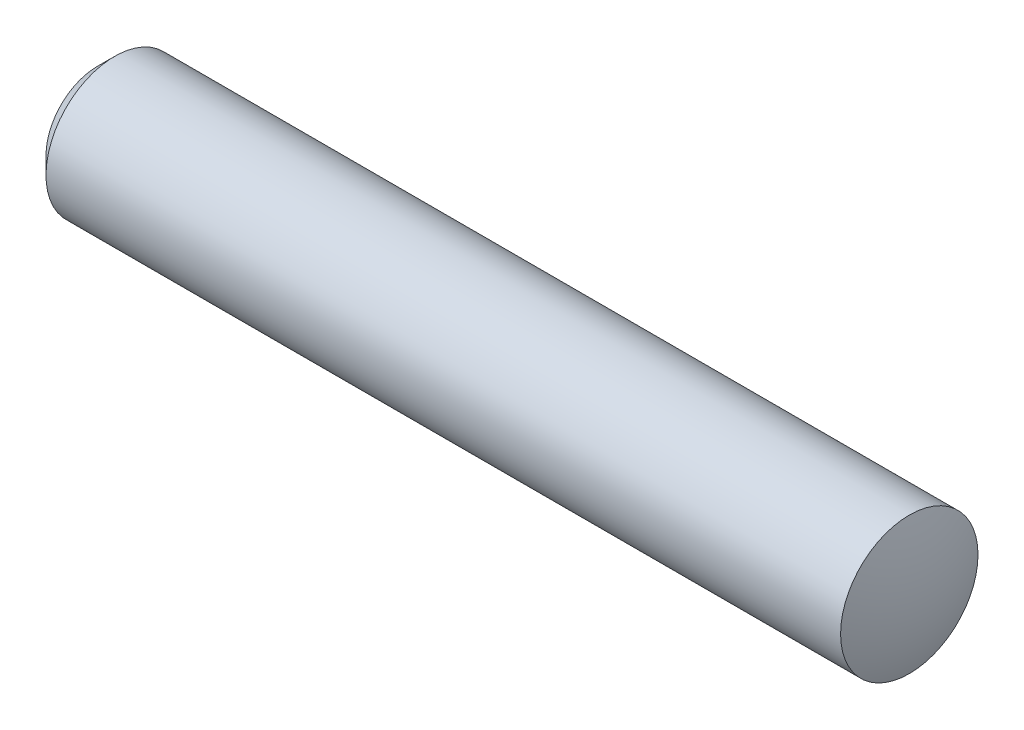
SolidWorks part; units mm, degrees
ref_plane "Front" through (0, 0, 0) normal (0, 0, 1) x (1, 0, 0)
ref_plane "Top" through (0, 0, 0) normal (0, 1, 0) x (1, 0, 0)
ref_plane "Right" through (0, 0, 0) normal (1, 0, 0) x (0, 0, -1)
sketch "Sketch1" plane through (0, 0, 0) normal (0, 0, 1) x (1, 0, 0)
  line L0 (-11.8977, 0) -> (11.8977, 0) construction
  line L1 (-12.1023, 1.5) -> (-11.6023, 2)
  line L2 (-11.6023, 2) -> (-6.1023, 2)
  line L3 (11.8977, 0) -> (11.8977, -7.427) construction
  line L4 (-11.8977, 0) -> (-11.8977, -2.1222) construction
  line L5 (-6.1023, 2) -> (-2.1023, 2)
  line L6 (-2.1023, 2) -> (11.5284, 2)
  line L7 (-7.8682, 16.2978) -> (10.1318, 16.2978) construction
  line L8 (-11.8977, 0) -> (-2.1023, 0)
  line L9 (-4.1023, 2) -> (-4.1023, 0) construction
  line L10 (-12.1023, 1.5) -> (-6.1023, 1.5) construction
  line L11 (-6.1023, 1.5) -> (-6.1023, 2) construction
  line L12 (-2.1023, 0) -> (11.8977, 0)
  line L13 (4.8977, 0) -> (4.8977, -0.4) construction
  line L14 (-9.1023, 1.5) -> (-9.1023, -0.4) construction
  line L15 (-9.1023, -0.4) -> (4.8977, -0.4) construction
  arc A0 (11.5284, 2) -> (11.8977, 0) centre (6.2977, 0) cw
  arc A1 (-12.1023, 1.5) -> (-11.8977, 0) centre (-17.4977, 0) cw
  arc A2 (-11.8977, -0.8204) -> (11.5284, -1.6339) centre (-2.1023, -56.45) cw construction
  dimension "re" = 5.6
  dimension "D1" = 0.5
  dimension "D2" = 45
  dimension "d" = 4
  dimension "bm" = 6
  dimension "b" = 14
  dimension "la" = 4
  dimension "l" = 18
  dimension "F" = 0.4
revolve "Revolve1" add sketch "Sketch1" angle 360 about L8
cosmetic thread "Cosmetic Thread1" [suppressed]
cosmetic thread "Cosmetic Thread2" [suppressed]
sketch "Sketch2" plane through (0, 0, 0) normal (0, 0, 1) x (1, 0, 0)
  line L0 (11.5284, 1.5) -> (11.817, 2)
  line L1 (11.817, 2) -> (11.817, 2.5774)
  line L2 (11.817, 2.5774) -> (11.2397, 2.5774)
  line L3 (11.2397, 2.5774) -> (11.2397, 2)
  line L4 (11.2397, 2) -> (11.5284, 1.5)
  line L5 (11.5284, -2) -> (11.5284, 2) construction
  line L6 (0, 0) -> (13.194, 0) construction
  line L7 (-2.1023, 2) -> (11.5284, 2) construction
  dimension "D1" = 3
revolve "Cut-Revolve1" [suppressed] cut sketch "Sketch2" angle 360 about L6
pattern_linear "LPattern1" [suppressed] count 18 along (1, 0, 0)
sketch "Sketch3" plane through (0, 0, 0) normal (0, 0, 1) x (1, 0, 0)
  line L0 (0, 0) -> (-12.6753, 0) construction
  line L1 (-11.6023, 1.5) -> (-11.3136, 2)
  line L2 (-11.3136, 2) -> (-11.3136, 2.5774)
  line L3 (-11.3136, 2.5774) -> (-11.891, 2.5774)
  line L4 (-11.891, 2.5774) -> (-11.891, 2)
  line L5 (-11.891, 2) -> (-11.6023, 1.5)
  line L6 (-11.6023, 2) -> (-6.1023, 2) construction
  line L7 (-11.6023, -2) -> (-11.6023, 2) construction
  dimension "D1" = 3
revolve "Cut-Revolve2" [suppressed] cut sketch "Sketch3" angle 360 about L0
pattern_linear "LPattern2" [suppressed] count 8 spacing 0.8 along (-1, 0, 0)
equation "\"la@Sketch1\" = \"l@Sketch1\" - \"b@Sketch1\""
equation "\"F@Sketch1\" = \"d@Sketch1\" / 10"
equation "\"D1@Cosmetic Thread1\" = \"bm@Sketch1\""
equation "\"D1@Cosmetic Thread2\" = \"b@Sketch1\""
equation "\"D1@Sketch2\" = \"D2@Cosmetic Thread2\""
equation "\"D1@LPattern1\" = \"b@Sketch1\" / \"p@LPattern1\""
equation "\"D1@Sketch3\" = \"D2@Cosmetic Thread1\""
equation "\"D1@LPattern2\" = \"bm@Sketch1\" / \"D3@LPattern2\""
